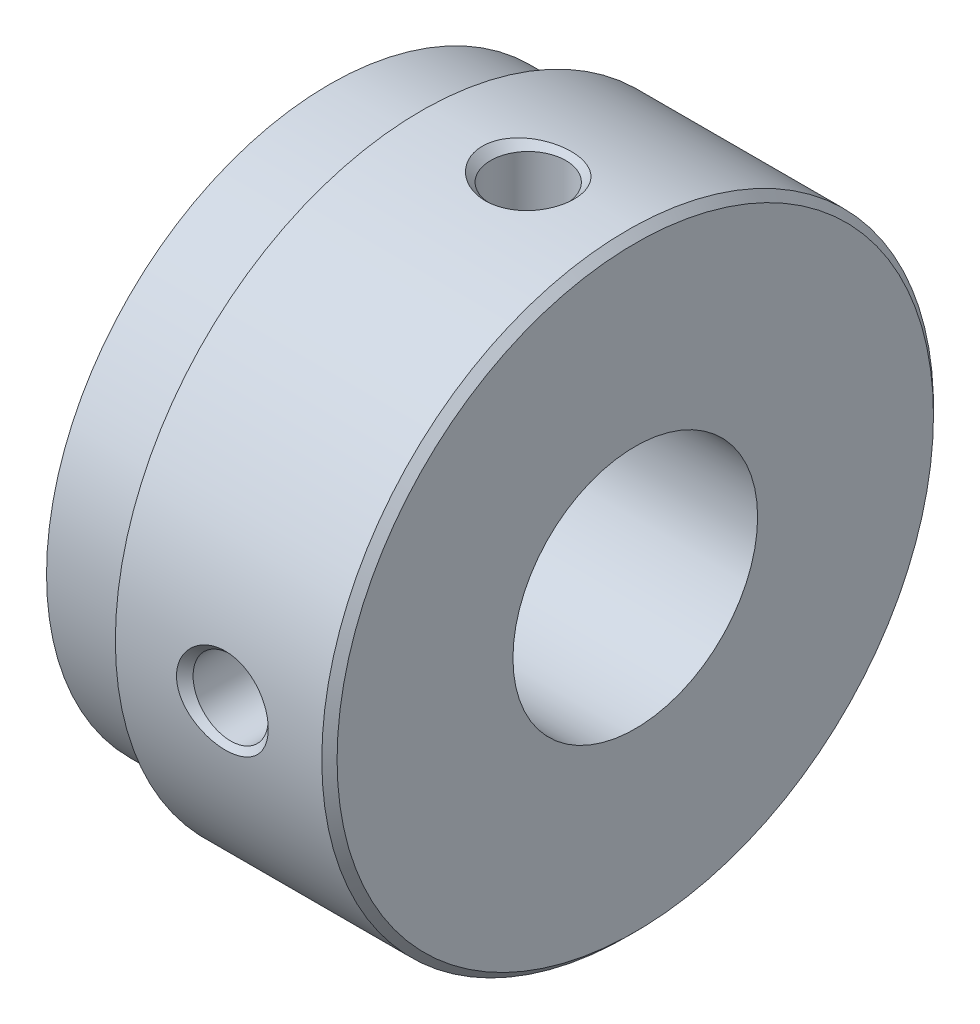
SolidWorks part; units mm, degrees
ref_plane "Front Plane" through (0, 0, 0) normal (0, 0, 1) x (1, 0, 0)
ref_plane "Top Plane" through (0, 0, 0) normal (0, 1, 0) x (1, 0, 0)
ref_plane "Right Plane" through (0, 0, 0) normal (1, 0, 0) x (0, 0, -1)
ref_plane "Plane1" through (0, 0, 0) normal (0, 0, 1) x (1, 0, 0)
sketch "Sketch1" plane through (0, 0, 0) normal (0, 0, 1) x (1, 0, 0)
  line L0 (0, 4) -> (10, 4)
  line L1 (10, 4) -> (10, 9.75)
  line L2 (10, 9.75) -> (9.75, 10)
  line L3 (9.75, 10) -> (3, 10)
  line L4 (3, 10) -> (3, 9.25)
  line L5 (3, 9.25) -> (0, 9.25)
  line L6 (0, 9.25) -> (0, 4)
  line L7 (10, 0) -> (0, 0) construction
revolve "Revolve1" add sketch "Sketch1" angle 360 about L7
ref_plane "Plane2" through (6.5, 0, 0) normal (1, 0, 0) x (0, 0, -1)
sketch "Sketch2" plane through (6.5, 0, 0) normal (1, 0, 0) x (0, 0, -1)
  line L0 (0, 10) -> (1.5, 10)
  line L1 (1.5, 10) -> (1.2295, 9.7295)
  line L2 (1.2295, 9.7295) -> (1.2295, 0)
  line L3 (1.2295, 0) -> (0, 0)
  line L4 (0, 0) -> (0, 10)
  line L5 (0, 0) -> (0, 10) construction
revolve "Cut-Revolve1" cut sketch "Sketch2" angle 360 about L5
ref_plane "Plane3" through (6.5, 0, 0) normal (1, 0, 0) x (0, 0, -1)
sketch "Sketch3" plane through (6.5, 0, 0) normal (1, 0, 0) x (0, 0, -1)
  line L0 (-10, 0) -> (-10, 1.5)
  line L1 (-10, 1.5) -> (-9.7295, 1.2295)
  line L2 (-9.7295, 1.2295) -> (0, 1.2295)
  line L3 (0, 1.2295) -> (0, 0)
  line L4 (0, 0) -> (-10, 0)
  line L5 (0, 0) -> (-10, 0) construction
revolve "Cut-Revolve2" cut sketch "Sketch3" angle 360 about L5
